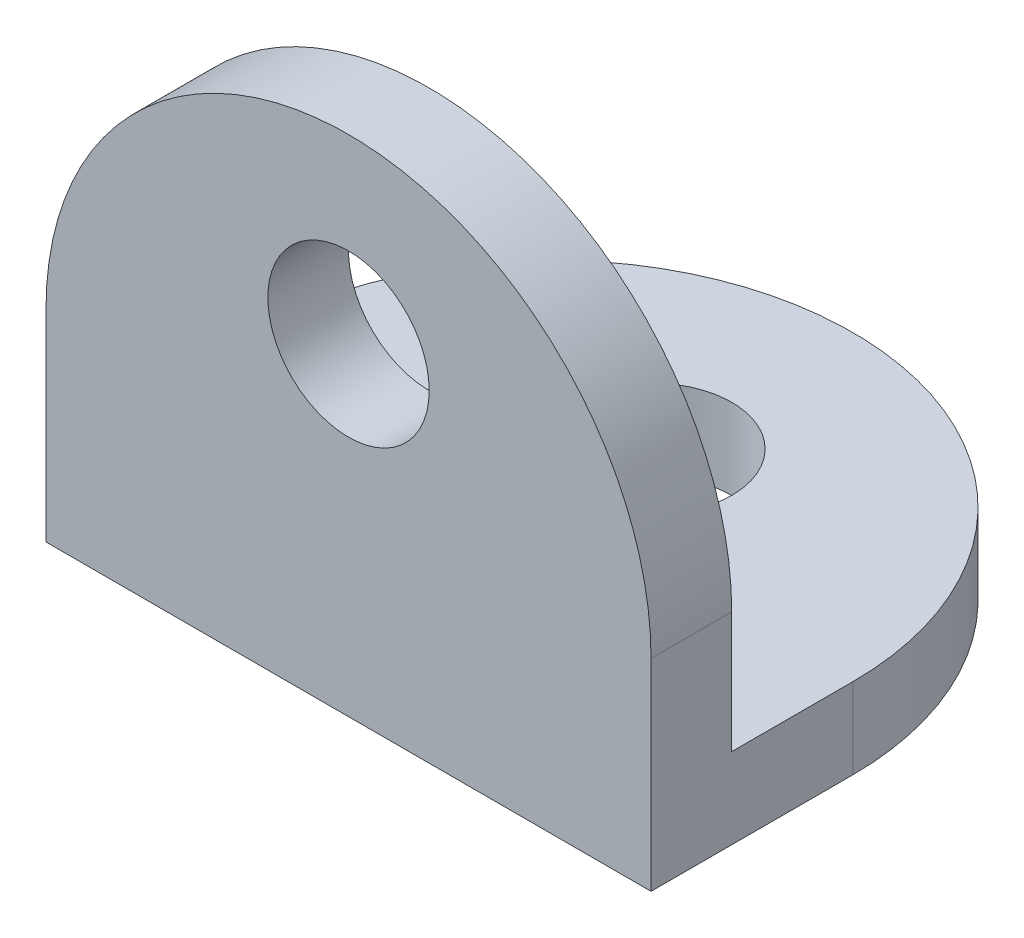
SolidWorks part; units mm, degrees
ref_plane "前视基准面" through (0, 0, 0) normal (0, 0, 1) x (1, 0, 0)
ref_plane "上视基准面" through (0, 0, 0) normal (0, 1, 0) x (1, 0, 0)
ref_plane "右视基准面" through (0, 0, 0) normal (1, 0, 0) x (0, 0, -1)
sketch "草图1" plane through (0, 0, 0) normal (0, 0, 1) x (1, 0, 0)
  line L1 (-7.5, 5) -> (7.5, 5)
  line L2 (-7.5, 5) -> (-7.5, 0)
  line L3 (-7.5, 0) -> (7.5, 0)
  line L4 (7.5, 5) -> (7.5, 0)
  line L5 (-7.5, 5) -> (7.5, 0) construction
  line L6 (-7.5, 0) -> (7.5, 5) construction
  arc A0 (-7.5, 5) -> (7.5, 5) centre (0, 5) cw
  circle A1 centre (0, 8) radius 2
  point P0 (0, 2.5)
  dimension "D3" = 4
  dimension "D1" = 15
  dimension "D2" = 5
  dimension "D4" = 5.5
sketch "草图2" plane through (0, 0, 0) normal (0, 1, 0) x (1, 0, 0)
  line L0 (-7.5, 0) -> (7.5, 0) construction
  line L1 (-7.5, 5) -> (7.5, 5)
  line L2 (-7.5, 5) -> (-7.5, 0)
  line L3 (-7.5, 0) -> (7.5, 0)
  line L4 (7.5, 5) -> (7.5, 0)
  line L5 (-7.5, 5) -> (7.5, 0) construction
  line L6 (-7.5, 0) -> (7.5, 5) construction
  arc A0 (-7.5, 5) -> (7.5, 5) centre (0, 5) cw
  circle A1 centre (0, 7.5) radius 2
  point P0 (0, 2.5)
  point P12 (0, 0)
  dimension "D3" = 4
  dimension "D1" = 5
  dimension "D2" = 15
  dimension "D4" = 7.5
extrude "凸台-拉伸1" add sketch "草图2" along normal blind 2 contours A0 L1 A1 | L4 L1 L2 L3
extrude "凸台-拉伸2" add sketch "草图1" against normal blind 2 contours L4 L1 L2 L3 | A0 L1 A1
